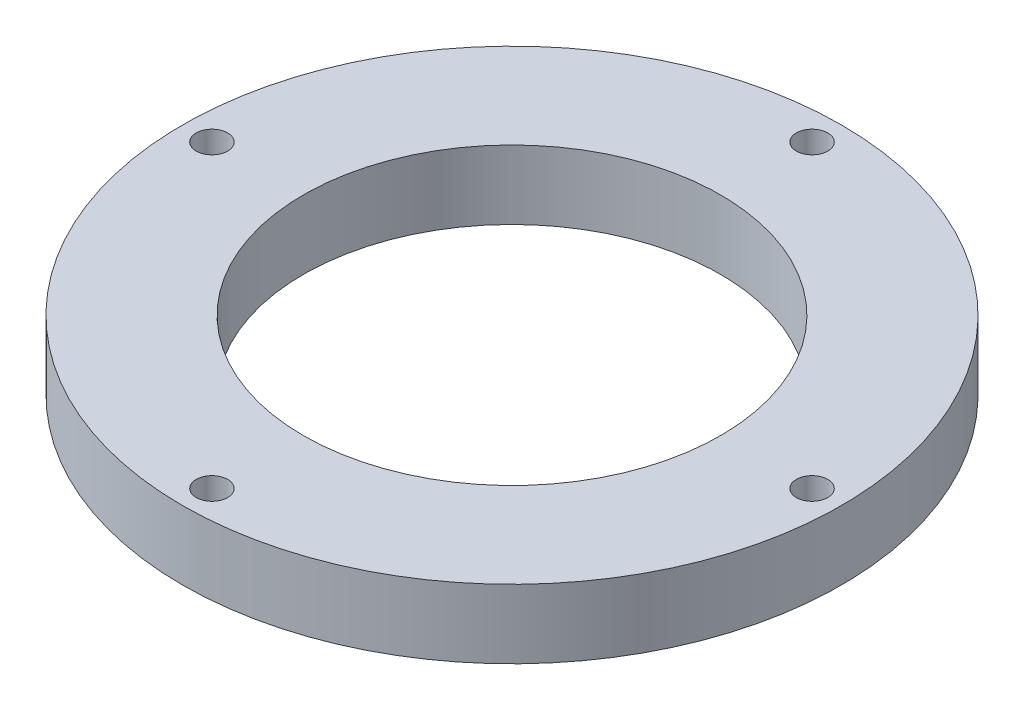
SolidWorks part; units mm, degrees
ref_plane "Front Plane" through (0, 0, 0) normal (0, 0, 1) x (1, 0, 0)
ref_plane "Top Plane" through (0, 0, 0) normal (0, 1, 0) x (1, 0, 0)
ref_plane "Right Plane" through (0, 0, 0) normal (1, 0, 0) x (0, 0, -1)
sketch "Sketch1" plane through (0, 0, 0) normal (0, 1, 0) x (1, 0, 0)
  circle A0 centre (0, 0) radius 21.2
  circle A1 centre (0, 0) radius 33.5
  dimension "D1" = 42.4
  dimension "D2" = 67
extrude "Boss-Extrude1" add sketch "Sketch1" along normal blind 7
sketch "Sketch2" plane through (0, 7, 0) normal (0, 1, 0) x (1, 0, 0)
  line L0 (0, 0) -> (0, 30.5) construction
  circle A0 centre (0, 30.5) radius 1.6
  circle A1 centre (30.5, 0) radius 1.6
  circle A2 centre (0, -30.5) radius 1.6
  circle A3 centre (-30.5, 0) radius 1.6
  point P13 (0, 0)
  dimension "D2" = 3.2
  dimension "D1" = 30.5
  dimension "D3" = 4
extrude "Cut-Extrude1" cut sketch "Sketch2" against normal through all
